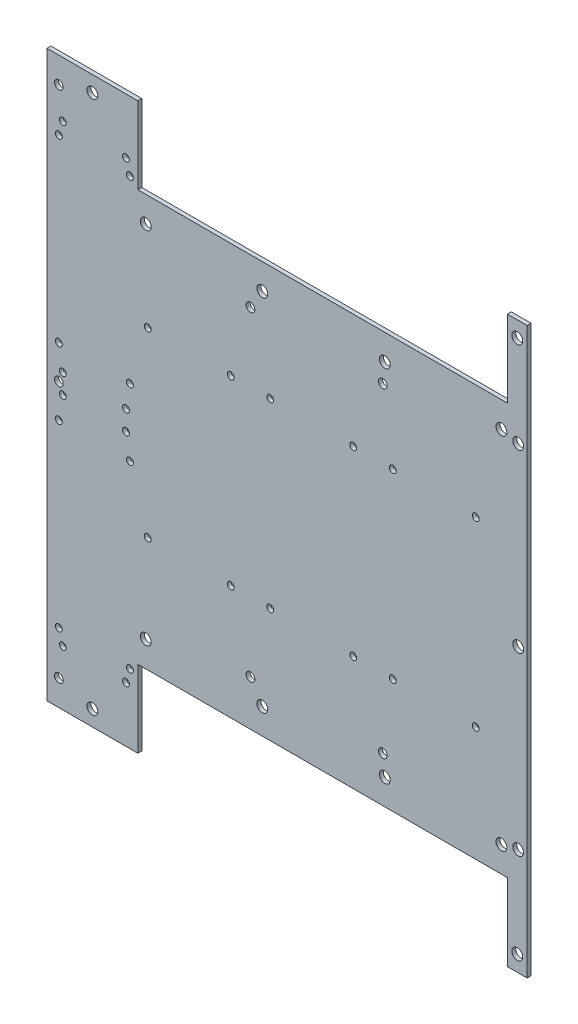
SolidWorks part; units mm, degrees
ref_plane "Front Plane" through (0, 0, 0) normal (0, 0, 1) x (1, 0, 0)
ref_plane "Top Plane" through (0, 0, 0) normal (0, 1, 0) x (1, 0, 0)
ref_plane "Right Plane" through (0, 0, 0) normal (1, 0, 0) x (0, 0, -1)
sketch "Motor and battery floor profile" plane through (0, 0, 0) normal (0, 0, 1) x (1, 0, 0)
  line L0 (-140, -143) -> (-94, -143)
  line L1 (-94, -143) -> (-94, -104)
  line L2 (-94, -104) -> (93, -104)
  line L3 (93, -104) -> (93, -143)
  line L4 (93, -143) -> (103, -143)
  line L5 (103, -143) -> (103, 143)
  line L6 (103, 143) -> (93, 143)
  line L7 (93, 143) -> (93, 104)
  line L8 (93, 104) -> (-94, 104)
  line L9 (-94, 104) -> (-94, 143)
  line L10 (-94, 143) -> (-140, 143)
  line L11 (-140, 143) -> (-140, -143)
  circle A0 centre (-90, -91) radius 2.75
  circle A1 centre (-90, 91) radius 2.75
  circle A2 centre (-31, -91) radius 2.75
  circle A3 centre (-31, 91) radius 2.75
  circle A4 centre (31, -91) radius 2.75
  circle A5 centre (31, 91) radius 2.75
  circle A6 centre (90, -91) radius 2.75
  circle A7 centre (90, 91) radius 2.75
  circle A8 centre (-134, -108) radius 1.75
  circle A9 centre (-134, -17) radius 1.75
  circle A10 centre (-134, 17) radius 1.75
  circle A11 centre (-134, 108) radius 1.75
  circle A12 centre (-98, -108) radius 1.75
  circle A13 centre (-98, -17) radius 1.75
  circle A14 centre (-98, 17) radius 1.75
  circle A15 centre (-98, 108) radius 1.75
  circle A16 centre (-89, -46) radius 1.75
  circle A17 centre (-89, 46) radius 1.75
  circle A18 centre (-47, -46) radius 1.75
  circle A19 centre (-47, 46) radius 1.75
  circle A20 centre (-27, -46) radius 1.75
  circle A21 centre (-27, 46) radius 1.75
  circle A22 centre (15, -46) radius 1.75
  circle A23 centre (15, 46) radius 1.75
  circle A24 centre (35, -46) radius 1.75
  circle A25 centre (35, 46) radius 1.75
  circle A26 centre (77, -46) radius 1.75
  circle A27 centre (77, 46) radius 1.75
  circle A28 centre (-117, -135) radius 2.75
  circle A29 centre (-117, 135) radius 2.75
  circle A30 centre (98, -135) radius 2.75
  circle A31 centre (98, 135) radius 2.75
  circle A32 centre (98.5, -89) radius 2.75
  circle A33 centre (98.5, 0) radius 2.75
  circle A34 centre (98.5, 89) radius 2.75
  circle A35 centre (-134, -130) radius 2.2
  circle A36 centre (-134, 0) radius 2.2
  circle A37 centre (-134, 130) radius 2.2
  circle A38 centre (-37, -81) radius 2.2
  circle A39 centre (-37, 81) radius 2.2
  circle A40 centre (30, -81) radius 2.2
  circle A41 centre (30, 81) radius 2.2
  circle A42 centre (-132, -115) radius 1.75
  circle A43 centre (-132, -5) radius 1.75
  circle A44 centre (-132, 5) radius 1.75
  circle A45 centre (-132, 115) radius 1.75
  circle A46 centre (-100, -115) radius 1.75
  circle A47 centre (-100, -5) radius 1.75
  circle A48 centre (-100, 5) radius 1.75
  circle A49 centre (-100, 115) radius 1.75
extrude "Motor and battery floor" add sketch "Motor and battery floor profile" along normal blind 2
